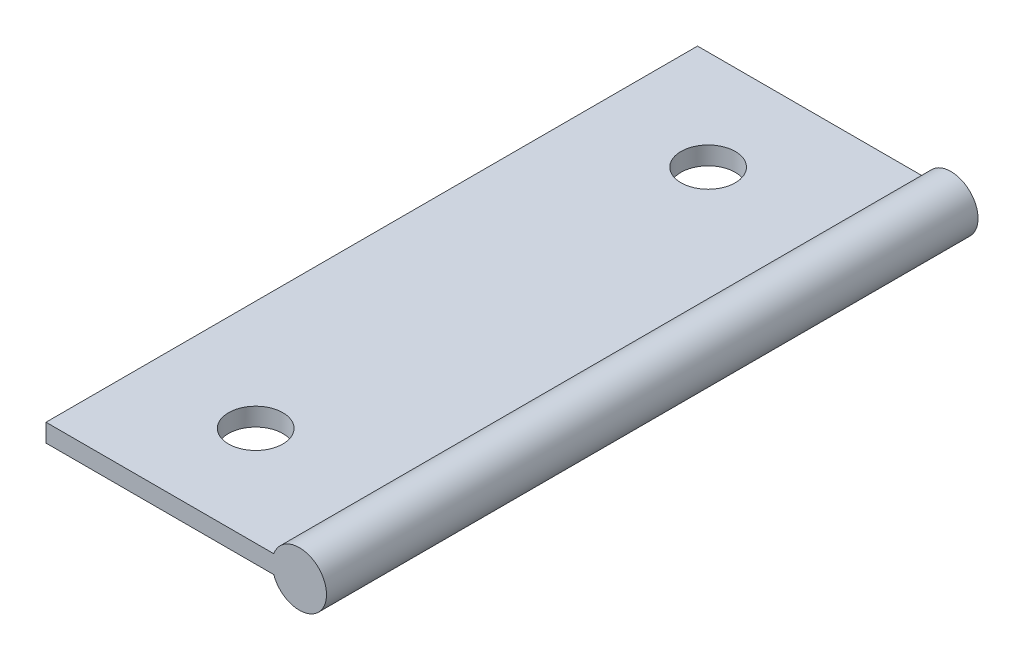
SolidWorks part; units mm, degrees
material "1.5714 (16NiCr4)"
ref_plane "Front" through (0, 0, 0) normal (0, 0, 1) x (1, 0, 0)
ref_plane "Top" through (0, 0, 0) normal (0, 1, 0) x (1, 0, 0)
ref_plane "Right" through (0, 0, 0) normal (1, 0, 0) x (0, 0, -1)
sketch "草图1" plane through (0, 0, 0) normal (0, 0, 1) x (1, 0, 0)
  line L0 (-1.4142, 0.5) -> (-14, 0.5)
  line L1 (-14, 0.5) -> (-14, -0.5)
  line L2 (-14, -0.5) -> (-1.4142, -0.5)
  arc A0 (-1.4142, -0.5) -> (-1.4142, 0.5) centre (0, 0) ccw
  dimension "D1" = 3
  dimension "D2" = 14
  dimension "D3" = 1
extrude "凸台-拉伸1" add sketch "草图1" along normal blind 36
sketch "草图2" plane through (0, 0.5, 0) normal (0, 1, 0) x (1, 0, 0)
  line L0 (-14, -18) -> (-1.4142, -18) construction
  line L1 (-14, -36) -> (-14, 0) construction
  line L2 (-1.4142, -36) -> (-1.4142, 0) construction
  circle A0 centre (-7.9142, -5.5) radius 1.5
  circle A2 centre (-7.9142, -30.5) radius 1.5
  dimension "D1" = 3
  dimension "D2" = 12.5
  dimension "D4" = 6.5
extrude "切除-拉伸1" cut sketch "草图2" against normal through all
